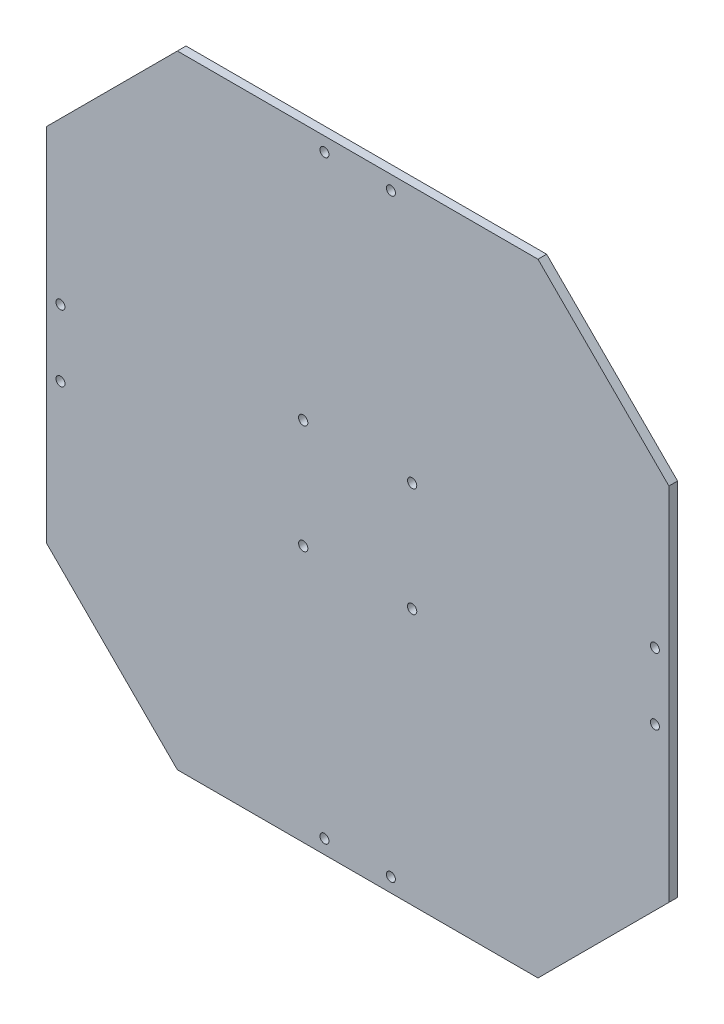
SolidWorks part; units mm, degrees
ref_plane "Front Plane" through (0, 0, 0) normal (0, 0, 1) x (1, 0, 0)
ref_plane "Top Plane" through (0, 0, 0) normal (0, 1, 0) x (1, 0, 0)
ref_plane "Right Plane" through (0, 0, 0) normal (1, 0, 0) x (0, 0, -1)
sketch "Sketch1" plane through (0, 0, 0) normal (0, 0, 1) x (1, 0, 0)
  line L1 (-88.94, 28.9481) -> (139.66, 28.9481)
  line L2 (-88.94, 28.9481) -> (-88.94, 257.5481)
  line L3 (-88.94, 257.5481) -> (139.66, 257.5481)
  line L4 (139.66, 28.9481) -> (139.66, 257.5481)
  line L5 (-88.94, 28.9481) -> (139.66, 257.5481) construction
  line L6 (-88.94, 257.5481) -> (139.66, 28.9481) construction
  line L10 (91.5768, 257.5481) -> (-88.94, 77.0313) construction
  line L11 (139.66, 209.4648) -> (-40.8567, 28.9481) construction
  line L14 (91.5768, 28.9481) -> (-88.94, 209.4648) construction
  line L17 (139.66, 77.0313) -> (-40.8567, 257.5481) construction
  line L19 (139.66, 77.0313) -> (91.5768, 28.9481)
  line L20 (-40.8567, 28.9481) -> (-88.94, 77.0313)
  line L21 (-88.94, 209.4648) -> (-40.8567, 257.5481)
  line L22 (91.5768, 257.5481) -> (139.66, 209.4648)
  point P0 (25.36, 143.2481)
  point P19 (-40.8567, 28.9481)
  point P20 (-40.8567, 28.9481)
extrude "Boss-Extrude1" add sketch "Sketch1" along normal blind 3.175 contours L22 L3 L21 L2 L20 L1 L19 L4
hole_wizard "M3 Clearance Hole1" positions "Sketch5" profile "Sketch4" hole size "M3" standard "AS" end condition up to next
sketch "Sketch5" plane through (0, 0, 3.175) normal (0, 0, 1) x (1, 0, 0)
  line L1 (45.36, 123.2481) -> (5.36, 123.2481)
  line L2 (45.36, 123.2481) -> (45.36, 163.2481)
  line L3 (45.36, 163.2481) -> (5.36, 163.2481)
  line L4 (5.36, 123.2481) -> (5.36, 163.2481)
  line L5 (45.36, 123.2481) -> (5.36, 163.2481) construction
  line L6 (45.36, 163.2481) -> (5.36, 123.2481) construction
  line L7 (139.66, 143.2481) -> (25.36, 143.2481) construction
  line L8 (139.66, 77.0313) -> (139.66, 209.4648) construction
  line L10 (-224.1373, 141.3824) -> (-188.4136, 91.5776)
  line L11 (25.36, 143.2481) -> (25.36, 257.5481) construction
  line L12 (-40.8567, 257.5481) -> (91.5768, 257.5481) construction
  point P11 (5.36, 163.2481)
  point P104 (45.36, 123.2481)
  point P105 (45.36, 163.2481)
  point P106 (5.36, 123.2481)
  dimension "D3" = 40
sketch "Sketch4" plane through (5.36, 163.2481, 3.175) normal (1, 0, 0) x (0, -1, 0)
  line L0 (0, 0) -> (0, 3.175)
  line L1 (0, 3.175) -> (1.7, 3.175)
  line L2 (1.7, 3.175) -> (1.7, 0)
  line L5 (1.7, 0) -> (0, 0)
  line L11 (0, -6.35) -> (0, 107.95) construction
  dimension "Thru Hole Dia." = 3.4
  dimension "Thru Hole Depth" = 3.175
sketch "Sketch6" plane through (0, 0, 3.175) normal (0, 0, 1) x (1, 0, 0)
  circle A0 centre (37.56, 252.3919) radius 1.651 construction
  circle A1 centre (13.16, 252.3919) radius 1.651 construction
  circle A2 centre (-83.7838, 155.4481) radius 1.651 construction
  circle A3 centre (-83.7838, 131.0481) radius 1.651 construction
  circle A4 centre (13.16, 34.1043) radius 1.651 construction
  circle A5 centre (37.56, 34.1043) radius 1.651 construction
  circle A6 centre (134.5038, 131.0481) radius 1.651 construction
  circle A7 centre (134.5038, 155.4481) radius 1.651 construction
  circle A8 centre (37.56, 252.3919) radius 1.651
  circle A9 centre (13.16, 252.3919) radius 1.651
  circle A10 centre (-83.7838, 155.4481) radius 1.651
  circle A11 centre (-83.7838, 131.0481) radius 1.651
  circle A12 centre (13.16, 34.1043) radius 1.651
  circle A13 centre (37.56, 34.1043) radius 1.651
  circle A14 centre (134.5038, 131.0481) radius 1.651
  circle A15 centre (134.5038, 155.4481) radius 1.651
extrude "Cut-Extrude1" cut sketch "Sketch6" against normal up to surface (3.175 mm away) up to face at (7.06, 163.2481, 0)
